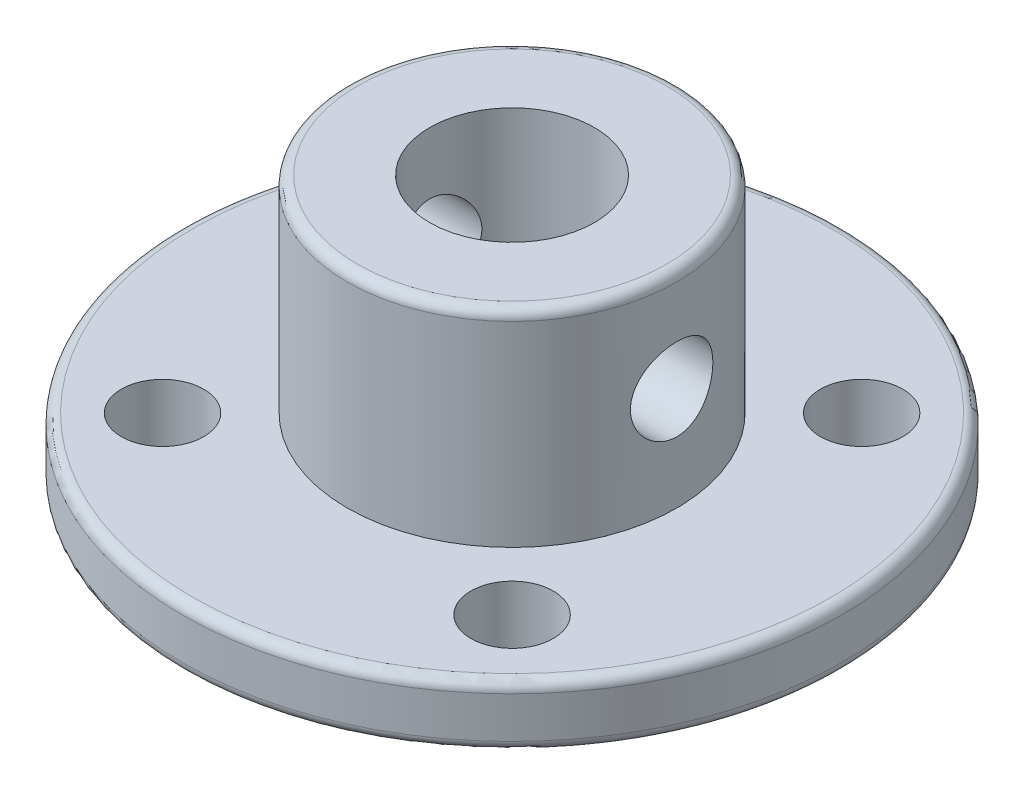
SolidWorks part; units mm, degrees
ref_plane "Front Plane" through (0, 0, 0) normal (0, 0, 1) x (1, 0, 0)
ref_plane "Top Plane" through (0, 0, 0) normal (0, 1, 0) x (1, 0, 0)
ref_plane "Right Plane" through (0, 0, 0) normal (1, 0, 0) x (0, 0, -1)
sketch "Sketch1" plane through (0, 0, 0) normal (0, 1, 0) x (1, 0, 0)
  circle A0 centre (0, 0) radius 16
  dimension "D1" = 32
extrude "Boss-Extrude1" add sketch "Sketch1" along normal blind 3
sketch "Sketch2" plane through (0, 3, 0) normal (0, 1, 0) x (1, 0, 0)
  circle A0 centre (0, 0) radius 8
  dimension "D1" = 16
extrude "Boss-Extrude2" add sketch "Sketch2" along normal blind 10
sketch "Sketch3" plane through (0, 13, 0) normal (0, 1, 0) x (1, 0, 0)
  circle A0 centre (0, 0) radius 4
  dimension "D1" = 8
extrude "Cut-Extrude1" cut sketch "Sketch3" against normal blind 13
sketch "Sketch4" plane through (0, 3, 0) normal (0, 1, 0) x (1, 0, 0)
  line L1 (5.6569, 5.6569) -> (11.3137, 11.3137) construction
  circle A0 centre (0, 0) radius 16 construction
  circle A1 centre (8.4853, 8.4853) radius 2
  circle A2 centre (8.4853, -8.4853) radius 2
  circle A3 centre (-8.4853, -8.4853) radius 2
  circle A4 centre (-8.4853, 8.4853) radius 2
  point P15 (0, 0)
  dimension "D1" = 4
  dimension "D2" = 4
extrude "Cut-Extrude3" cut sketch "Sketch4" against normal blind 3
sketch "Sketch6" plane through (0, 0, 0) normal (1, 0, 0) x (0, 0, -1)
  line L0 (0, 0) -> (0, 8) construction
  circle A0 centre (0, 8) radius 2
  dimension "D2" = 4
  dimension "D1" = 8
extrude "Cut-Extrude4" cut sketch "Sketch6" against normal blind 24 and the other way blind 10
fillet "Fillet1" radius 0.5 1 edges at (0, 0, 16)
fillet "Fillet3" radius 0.5 2 edges at (0, 13, 8) (0, 3, 16)
